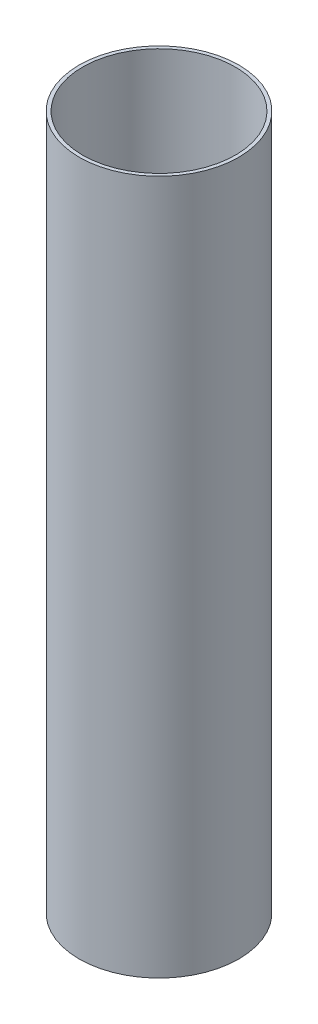
SolidWorks part; units mm, degrees
ref_plane "Front Plane" through (0, 0, 0) normal (0, 0, 1) x (1, 0, 0)
ref_plane "Top Plane" through (0, 0, 0) normal (0, 1, 0) x (1, 0, 0)
ref_plane "Right Plane" through (0, 0, 0) normal (1, 0, 0) x (0, 0, -1)
sketch "Sketch1" plane through (0, 0, 0) normal (0, 1, 0) x (1, 0, 0)
  circle A0 centre (0, 0) radius 110
  dimension "D1" = 220
extrude "Extrude-Thin1" add sketch "Sketch1" along normal blind 1000 thin
